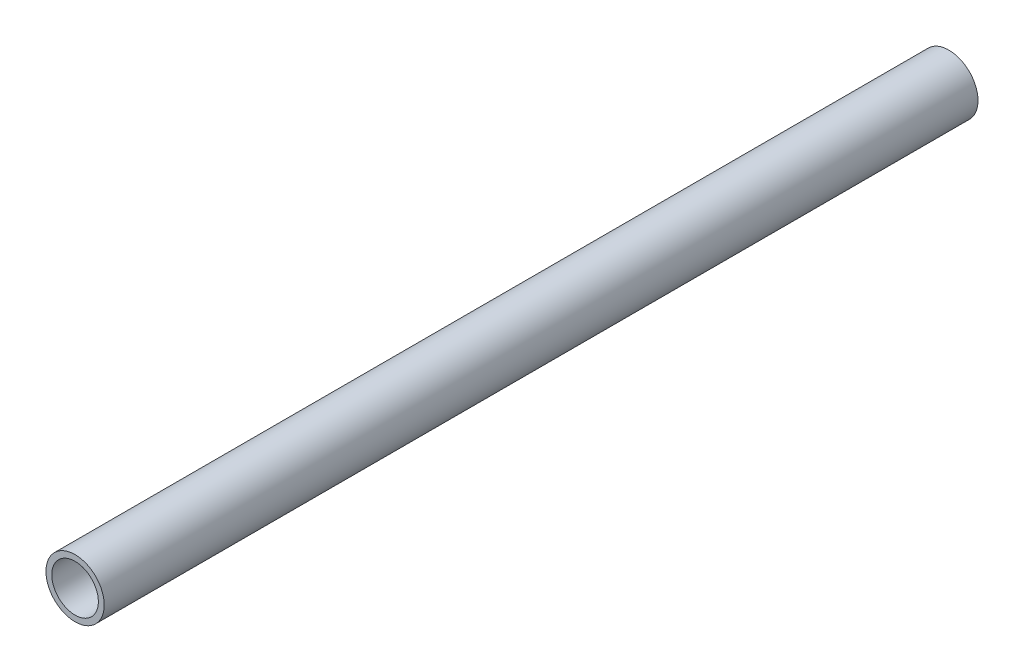
SolidWorks part; units mm, degrees
material "EM-CF"
ref_plane "Płaszczyzna przednia" through (0, 0, 0) normal (0, 0, 1) x (1, 0, 0)
ref_plane "Płaszczyzna górna" through (0, 0, 0) normal (0, 1, 0) x (1, 0, 0)
ref_plane "Płaszczyzna prawa" through (0, 0, 0) normal (1, 0, 0) x (0, 0, -1)
sketch "Szkic1" plane through (0, 0, 0) normal (0, 0, 1) x (1, 0, 0)
  circle A0 centre (0, 0) radius 8
  circle A1 centre (0, 0) radius 10
  dimension "D1" = 2
  dimension "D2" = 20
extrude "Dodanie-wyciągnięcie1" add sketch "Szkic1" along normal blind 300
